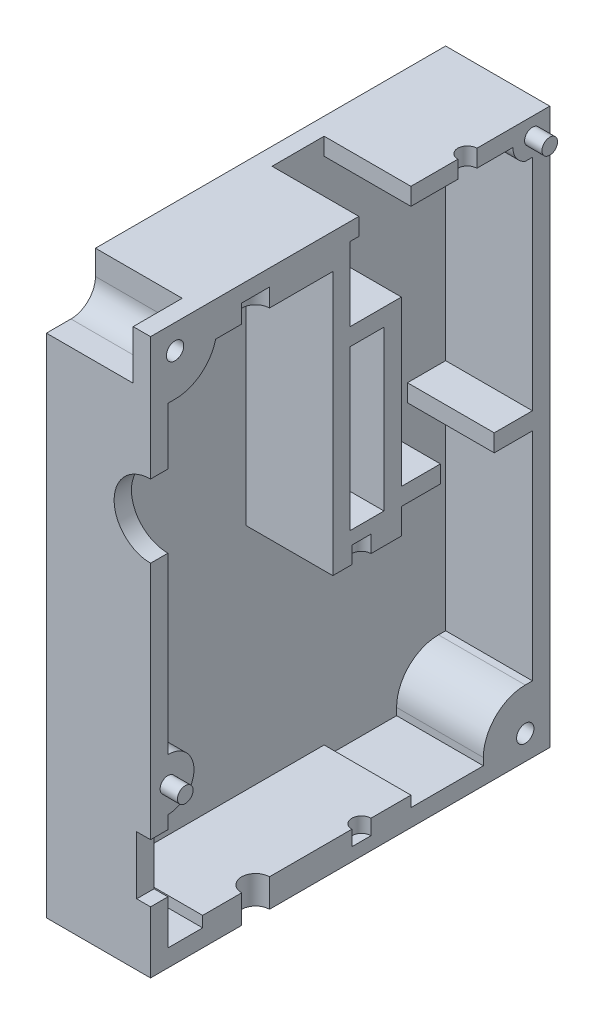
SolidWorks part; units mm, degrees
ref_plane "前视基准面" through (0, 0, 0) normal (0, 0, 1) x (1, 0, 0)
ref_plane "上视基准面" through (0, 0, 0) normal (0, 1, 0) x (1, 0, 0)
ref_plane "右视基准面" through (0, 0, 0) normal (1, 0, 0) x (0, 0, -1)
other "Configuration Table"
sketch "草图1" plane through (0, 0, 0) normal (1, 0, 0) x (0, 0, -1)
  line L1 (-23, 32) -> (23, 32)
  line L2 (-23, 32) -> (-23, -32)
  line L3 (-23, -32) -> (23, -32)
  line L4 (23, 32) -> (23, -32)
  line L5 (-23, 32) -> (23, -32) construction
  line L6 (-23, -32) -> (23, 32) construction
  point P0 (0, 0)
  dimension "D1" = 64
  dimension "D2" = 46
extrude "凸台-拉伸1" add sketch "草图1" along normal blind 12
shell "抽壳1" thickness 2
sketch "草图3" plane through (2, 0, 0) normal (1, 0, 0) x (0, 0, -1)
  line L10 (20.175, -24.35) -> (21, -24.35) construction
  line L23 (20.175, -24.35) -> (21, -24.35)
  line L45 (5.9, 0.6) -> (5.9, -2.35) construction
  line L46 (16.6, 0.6) -> (16.6, 2.6) construction
  line L61 (21, -30) -> (21, 30)
  line L62 (-21, -30) -> (21, -30)
  line L63 (-21, 30) -> (-21, -30)
  line L64 (21, 30) -> (-21, 30)
  line L65 (21, 0.6) -> (21, 2.6)
  line L67 (-21, 30) -> (-21, 24.35)
  line L68 (0, 30) -> (-21, 30)
  line L69 (10.4, 2.6) -> (10.4, 0.6) construction
  line L70 (5.9, 2.6) -> (10.4, 2.6) construction
  line L71 (5.9, 21.5) -> (5.9, 2.6) construction
  line L72 (0, 19.5) -> (3.9, 19.5) construction
  line L73 (3.9, 19.5) -> (3.9, 1.15) construction
  line L74 (0, 1.15) -> (0, 19.5) construction
  line L75 (3.9, 1.15) -> (0, 1.15) construction
  line L76 (5.9, -2.35) -> (-2, -2.35) construction
  line L77 (10.4, 0.6) -> (5.9, 0.6) construction
  line L78 (21, 0.6) -> (16.6, 0.6) construction
  line L79 (16.6, 2.6) -> (21, 2.6) construction
  line L80 (-2, 28) -> (-15.4953, 28) construction
  line L81 (-2, -2.35) -> (-2, 28) construction
  line L82 (0, 30) -> (0, 21.5) construction
  line L83 (0, 21.5) -> (5.9, 21.5) construction
  line L84 (5.9, 0.6) -> (5.9, -2.35)
  line L85 (16.6, 0.6) -> (16.6, 2.6)
  line L86 (10.4, 2.6) -> (10.4, 0.6)
  line L87 (5.9, 2.6) -> (10.4, 2.6)
  line L88 (5.9, 21.5) -> (5.9, 2.6)
  line L89 (0, 19.5) -> (3.9, 19.5)
  line L90 (3.9, 19.5) -> (3.9, 1.15)
  line L91 (0, 1.15) -> (0, 19.5)
  line L92 (3.9, 1.15) -> (0, 1.15)
  line L93 (5.9, -2.35) -> (-2, -2.35)
  line L94 (10.4, 0.6) -> (5.9, 0.6)
  line L95 (21, 0.6) -> (16.6, 0.6)
  line L96 (16.6, 2.6) -> (21, 2.6)
  line L97 (-2, 28) -> (-15.4953, 28)
  line L98 (-2, -2.35) -> (-2, 28)
  line L99 (0, 30) -> (0, 21.5)
  line L100 (0, 21.5) -> (5.9, 21.5)
  line L105 (21, -24.35) -> (21, -30)
  line L107 (21, -30) -> (15.35, -30)
  line L108 (-21, -10.7) -> (-21, -16.7)
  line L109 (18.75, 30) -> (21, 30)
  line L110 (21, 30) -> (21, 27.9)
  line L114 (15.35, -30) -> (15.35, -29.175) construction
  line L115 (15.35, -30) -> (15.35, -29.175)
  line L116 (-20.175, 24.35) -> (-21, 24.35) construction
  line L117 (-20.175, 24.35) -> (-21, 24.35)
  line L119 (21, 27.9) -> (20.1922, 27.9) construction
  line L120 (21, 27.9) -> (20.1922, 27.9)
  arc A0 (-20.175, 24.35) -> (-15.4953, 28) centre (-20.175, 29.175) ccw construction
  arc A1 (-20.175, 24.35) -> (-15.4953, 28) centre (-20.175, 29.175) ccw
  arc A10 (-21, -16.7) -> (-21, -10.7) centre (-21, -13.7) ccw construction
  arc A12 (-21, -16.7) -> (-21, -10.7) centre (-21, -13.7) ccw
  arc A13 (18.75, 30) -> (20.1922, 27.9) centre (21, 30) ccw construction
  arc A14 (18.75, 30) -> (20.1922, 27.9) centre (21, 30) ccw
  arc A17 (20.175, -24.35) -> (15.35, -29.175) centre (20.175, -29.175) ccw construction
  arc A18 (20.175, -24.35) -> (15.35, -29.175) centre (20.175, -29.175) ccw
  dimension "D1" = 0
extrude "凸台-拉伸6" add sketch "草图3" along normal up to surface (10 mm away) up to face at (12, 0, 0)
sketch "草图4" plane through (0, 0, 0) normal (-1, 0, 0) x (0, 0, 1)
  line L0 (-20.175, -26.35) -> (-23, -26.35)
  line L1 (-23, -32) -> (-23, 32) construction
  line L2 (-23, -32) -> (-23, -26.35)
  line L3 (23, -32) -> (-23, -32) construction
  line L4 (-17.3822, -32) -> (-23, -32)
  line L5 (-17.35, -29.175) -> (-17.35, -32)
  line L6 (-17.35, -32) -> (-17.3822, -32)
  line L7 (20.175, 26.35) -> (23, 26.35)
  line L8 (23, 32) -> (23, -32) construction
  line L9 (17.35, 29.175) -> (17.35, 32)
  line L10 (-23, 32) -> (23, 32) construction
  line L11 (17.35, 32) -> (23, 32)
  line L12 (23, 32) -> (23, 26.35)
  circle A0 centre (-20.175, -29.175) radius 1
  circle A1 centre (20.175, 29.175) radius 1
  arc A2 (-17.35, -29.175) -> (-20.175, -26.35) centre (-20.175, -29.175) ccw
  arc A3 (-15.35, -29.175) -> (-20.175, -24.35) centre (-20.175, -29.175) ccw construction
  arc A4 (17.35, 29.175) -> (20.175, 26.35) centre (20.175, 29.175) ccw
  arc A5 (15.4953, 28) -> (20.175, 24.35) centre (20.175, 29.175) ccw construction
  dimension "D1" = 2
  dimension "D2" = 2
  dimension "D3" = 2
  dimension "D4" = 2
extrude "切除-拉伸1" cut sketch "草图4" against normal offset from surface (10 mm away) 2 up to face at (12, 3.9369, -4.8166)
sketch "草图7" plane through (0, 0, 0) normal (-1, 0, 0) x (0, 0, 1)
  circle A0 centre (-20.175, -29.175) radius 1 construction
  circle A1 centre (-20.175, -29.175) radius 1
  circle A2 centre (20.175, 29.175) radius 1 construction
  circle A3 centre (20.175, 29.175) radius 1
extrude "切除-拉伸3" cut sketch "草图7" against normal up to next
sketch "草图8" plane through (0, 0, 0) normal (-1, 0, 0) x (0, 0, 1)
  circle A0 centre (-21, 30) radius 1 construction
  circle A1 centre (-21, 30) radius 1 construction
  circle A4 centre (21, -13.7) radius 1 construction
  circle A5 centre (21, -13.7) radius 1 construction
  circle A6 centre (-21, 30) radius 0.9
  circle A8 centre (21, -13.7) radius 0.9
  dimension "D1" = 0.1
  dimension "D2" = 0.1
extrude "凸台-拉伸7" add sketch "草图8" against normal blind 2 from surface at -12 starting at face at (12, -29.175, -21.175)
sketch "草图13" plane through (0, 0, 0) normal (-1, 0, 0) x (0, 0, 1)
  line L1 (-7, -28.75) -> (17, -28.75)
  line L2 (-7, -28.75) -> (-7, -30)
  line L3 (-7, -30) -> (17, -30)
  line L4 (17, -28.75) -> (17, -30)
extrude "凸台-拉伸8" add sketch "草图13" against normal up to surface (12 mm away) up to face at (12, -13.7, 20.1)
sketch "草图9" plane through (0, -32, 0) normal (0, -1, 0) x (1, 0, 0)
  line L0 (12, 23) -> (12, -23) construction
  line L1 (12, 9.3) -> (12, 12.5)
  arc A0 (12, 9.3) -> (12, 12.5) centre (12, 10.9) cw
  arc A1 (12, 9.3) -> (12, 12.5) centre (12, 10.9) ccw construction
extrude "切除-拉伸4" cut sketch "草图9" against normal up to next
sketch "草图10" plane through (0, -32, 0) normal (0, -1, 0) x (1, 0, 0)
  line L0 (12, 9.3) -> (12, -23) construction
  line L1 (12, -2.4) -> (12, -0.2)
  arc A0 (12, -2.4) -> (12, -0.2) centre (12, -1.3) cw
  arc A1 (12, -2.4) -> (12, -0.2) centre (12, -1.3) ccw construction
sketch "草图11" plane through (0, 32, 0) normal (0, 1, 0) x (1, 0, 0)
  line L0 (12, 23) -> (12, -23) construction
  line L1 (12, 12.4) -> (12, 14.6)
  arc A0 (12, 12.4) -> (12, 14.6) centre (12, 13.5) cw
  arc A1 (12, 12.4) -> (12, 14.6) centre (12, 13.5) ccw construction
extrude "切除-拉伸5" cut sketch "草图11" against normal up to next
sketch "草图12" plane through (0, 32, 0) normal (0, 1, 0) x (1, 0, 0)
  line L0 (12, -12.5) -> (12, -9.3)
  line L1 (12, 12.4) -> (12, -23) construction
  arc A0 (12, -12.5) -> (12, -9.3) centre (12, -10.9) cw
  arc A1 (12, -12.5) -> (12, -9.3) centre (12, -10.9) ccw construction
extrude "切除-拉伸6" cut sketch "草图12" against normal up to next from surface
extrude "切除-拉伸7" cut sketch "草图10" against normal up to surface (30.1 mm away) from surface at -1.5
sketch "草图14" plane through (0, 0, 23) normal (0, 0, 1) x (1, 0, 0)
  line L0 (12, 32) -> (12, -32) construction
  line L1 (12, 17.79) -> (12, 9.39)
  arc A0 (12, 9.39) -> (12, 17.79) centre (12, 13.59) cw
  arc A2 (12, 9.39) -> (12, 17.79) centre (12, 13.59) ccw construction
extrude "切除-拉伸8" cut sketch "草图14" against normal up to next
sketch "草图15" plane through (0, 32, 0) normal (0, 1, 0) x (1, 0, 0)
  line L0 (12, 12.4) -> (12, -23) construction
  line L1 (12, 7) -> (2, 7)
  line L2 (12, 7) -> (12, 1)
  line L3 (12, 1) -> (2, 1)
  line L4 (2, 7) -> (2, 1)
  line L5 (22, 7) -> (12, 7) construction
  line L6 (0, 23) -> (0, -17.35) construction
  line L7 (12, 1) -> (22, 1) construction
  dimension "D1" = 2
extrude "电机线切除-拉伸9" cut sketch "草图15" against normal up to next
sketch "草图16" plane through (0, 0, 23) normal (0, 0, 1) x (1, 0, 0)
  line L0 (12, 9.39) -> (12, -32) construction
  line L1 (12, -18.2) -> (10.4, -18.2)
  line L2 (12, -18.2) -> (12, -24.9)
  line L3 (12, -24.9) -> (10.4, -24.9)
  line L4 (10.4, -18.2) -> (10.4, -24.9)
  line L5 (13.6, -18.2) -> (12, -18.2) construction
  line L6 (12, -24.9) -> (13.6, -24.9) construction
extrude "拨杆切除-拉伸10" cut sketch "草图16" against normal up to next
